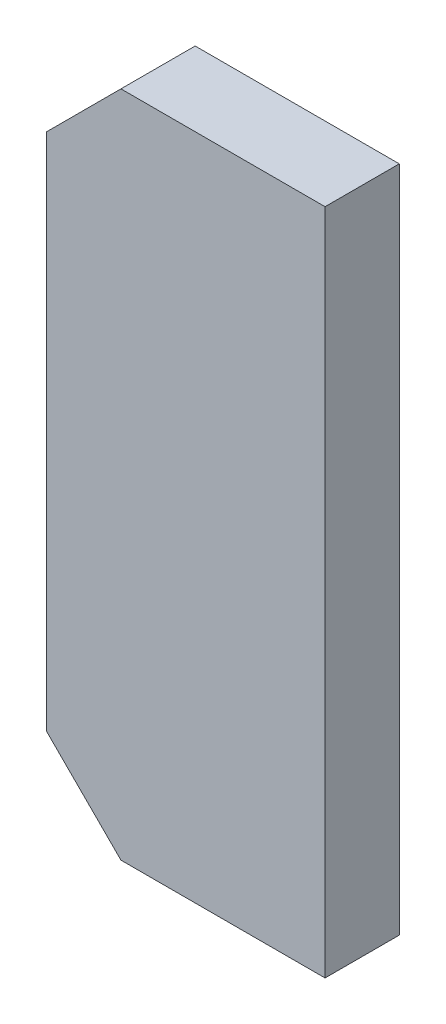
SolidWorks part; units mm, degrees
material "Rubber"
ref_plane "Front Plane" through (0, 0, 0) normal (0, 0, 1) x (1, 0, 0)
ref_plane "Top Plane" through (0, 0, 0) normal (0, 1, 0) x (1, 0, 0)
ref_plane "Right Plane" through (0, 0, 0) normal (1, 0, 0) x (0, 0, -1)
sketch "Sketch1" plane through (0, 0, 0) normal (0, 0, 1) x (1, 0, 0)
  line L0 (-50.8, 520.7) -> (-50.8, 12.7) construction
  line L1 (-50.8, 419.1) -> (-3.175, 419.1)
  line L2 (-50.8, 419.1) -> (-50.8, 533.4)
  line L3 (-50.8, 533.4) -> (-3.175, 533.4)
  line L4 (-3.175, 419.1) -> (-3.175, 533.4)
  line L5 (-3.175, 533.4) -> (-3.175, 0) construction
  line L6 (-3.175, 533.4) -> (-38.1, 533.4) construction
  dimension "D1" = 114.3
extrude "Boss-Extrude1" add sketch "Sketch1" along normal blind 12.7
chamfer "Chamfer1" distance 12.7 angle 45 2 edges at (-50.8, 533.4, 6.35) (-50.8, 419.1, 6.35)
sketch "Sketch2" [suppressed] plane through (0, 0, 12.7) normal (0, 0, 1) x (1, 0, 0)
  line L0 (-38.1, 520.7) -> (-25.4, 533.4) construction
  line L1 (-25.4, 0) -> (-38.1, 12.7) construction
  line L2 (-38.1, 520.7) -> (-38.1, 12.7) construction
  line L3 (-38.1, 520.7) -> (-25.4, 533.4)
  line L4 (-25.4, 0) -> (-38.1, 12.7)
  line L5 (-38.1, 520.7) -> (-38.1, 12.7)
  line L6 (-25.4, 533.4) -> (-50.8, 533.4)
  line L7 (-50.8, 533.4) -> (-50.8, 0)
  line L8 (-50.8, 0) -> (-25.4, 0)
  line L9 (-50.8, 520.7) -> (-50.8, 12.7) construction
extrude "Cut-Extrude1" [suppressed] cut sketch "Sketch2" against normal through all
